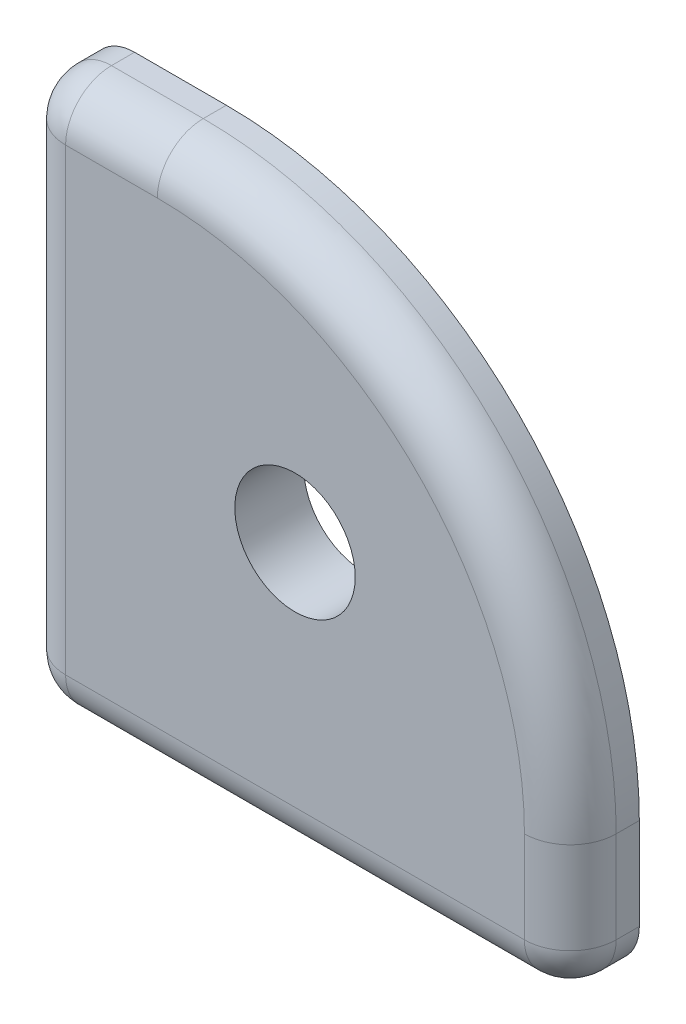
SolidWorks part; units mm, degrees
material "ABS"
ref_plane "Front Plane" through (0, 0, 0) normal (0, 0, 1) x (1, 0, 0)
ref_plane "Top Plane" through (0, 0, 0) normal (0, 1, 0) x (1, 0, 0)
ref_plane "Right Plane" through (0, 0, 0) normal (1, 0, 0) x (0, 0, -1)
sketch "Sketch1" plane through (0, 0, 0) normal (0, 0, 1) x (1, 0, 0)
  line L0 (20.386, 25.381) -> (21.402, 25.381)
  line L1 (20.894, 24.873) -> (20.894, 25.889)
  line L2 (20.386, 25.381) -> (21.402, 25.381)
  line L3 (20.894, 24.873) -> (20.894, 25.889)
  line L10 (1.844, 41.256) -> (1.844, 9.506)
  line L11 (5.019, 6.331) -> (36.769, 6.331)
  line L12 (39.944, 9.506) -> (39.944, 15.856)
  line L13 (5.019, 44.431) -> (11.369, 44.431)
  arc A2 (5.019, 44.431) -> (1.844, 41.256) centre (5.019, 41.256) ccw
  arc A3 (1.844, 9.506) -> (5.019, 6.331) centre (5.019, 9.506) ccw
  arc A4 (36.769, 6.331) -> (39.944, 9.506) centre (36.769, 9.506) ccw
  circle A5 centre (20.894, 25.381) radius 4.1656
  arc A6 (39.944, 15.856) -> (11.369, 44.431) centre (11.369, 15.856) ccw
  point P4 (22.6962, 27.4938)
  point P5 (19.0918, 23.2681)
extrude "Extrude1" add sketch "Sketch1" along normal blind 4.7752 contours L12 A6 L13 A2 L10 A3 L11 A4 A5
fillet "Fillet1" radius 3.175 8 edges at (2.774, 43.5011, 4.7752) (1.844, 25.381, 4.7752) (2.774, 7.2609, 4.7752) (20.894, 6.331, 4.7752) (39.0141, 7.2609, 4.7752) (39.944, 12.681, 4.7752) (31.5746, 36.0616, 4.7752) (8.194, 44.431, 4.7752)
sketch "Sketch2" plane through (0, 0, 0) normal (0, 0, -1) x (-1, 0, 0)
  circle A0 centre (-29.911, 10.649) radius 1.2065
  circle A1 centre (-11.877, 40.113) radius 1.2065
extrude "Extrude2" add sketch "Sketch2" along normal blind 2.4892
fillet "Fillet2" radius 1.2065 2 edges at (28.7045, 10.649, -2.4892) (10.6705, 40.113, -2.4892)
